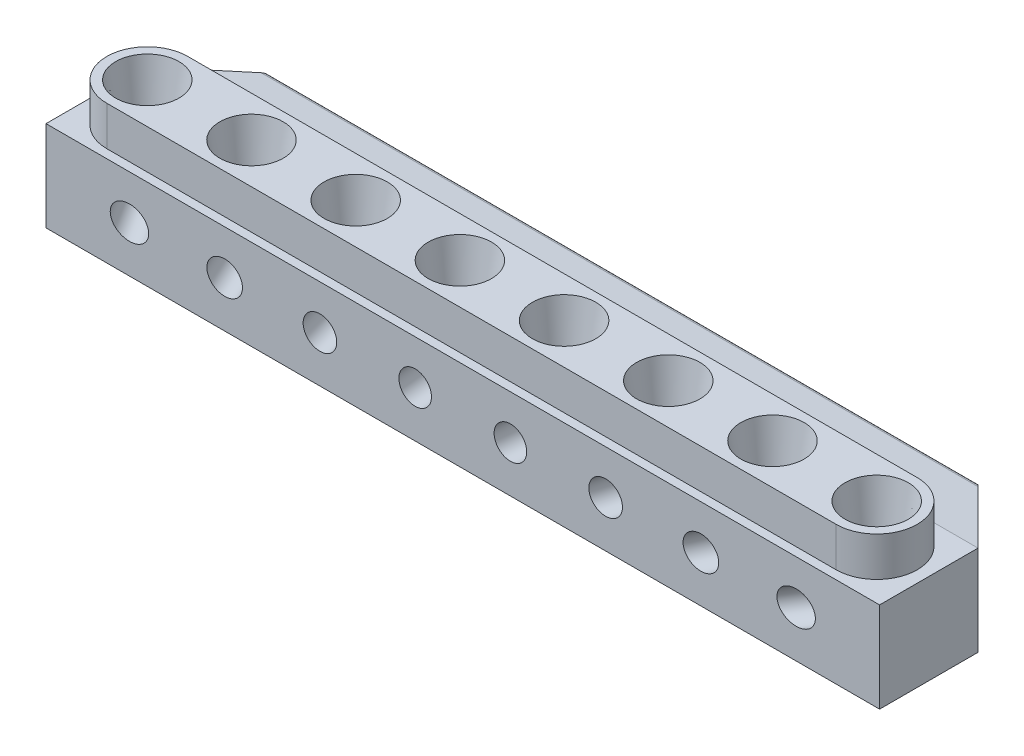
SolidWorks part; units mm, degrees
ref_plane "Front Plane" through (0, 0, 0) normal (0, 0, 1) x (1, 0, 0)
ref_plane "Top Plane" through (0, 0, 0) normal (0, 1, 0) x (1, 0, 0)
ref_plane "Right Plane" through (0, 0, 0) normal (1, 0, 0) x (0, 0, -1)
sketch "Sketch1" plane through (0, 0, 0) normal (0, 1, 0) x (1, 0, 0)
  line L0 (-53.7465, 0) -> (53.7465, 0) construction
  line L1 (-36, 4.25) -> (36, 4.25)
  line L2 (-36, 4.25) -> (-36, -4.25)
  line L3 (-36, -4.25) -> (36, -4.25)
  line L4 (36, 4.25) -> (36, -4.25)
  line L5 (0, 28.9014) -> (0, -25.6338) construction
  dimension "D1" = 8.5
  dimension "D2" = 72
extrude "Boss-Extrude1" add sketch "Sketch1" along normal blind 11.2
ref_plane "Plane1" through (-31.5, 0, 0) normal (-1, 0, 0) x (0, 0, 1)
sketch "Sketch2" plane through (-31.5, 0, 0) normal (-1, 0, 0) x (0, 0, 1)
  line L0 (0, 0) -> (0, 15.76) construction
  line L1 (-2.7346, 11.2) -> (-1.0108, 0)
  line L2 (-4.25, 11.2) -> (4.25, 11.2) construction
  line L4 (-2.7346, 11.2) -> (0, 11.2)
  line L5 (0, 11.2) -> (0, 0)
  line L7 (-4.25, 0) -> (4.25, 0) construction
  line L8 (-1, 0) -> (0, 0)
  line L9 (-3.0651, 13.3473) -> (-1.2355, 1.4598) construction
  line L10 (3.0651, 13.3473) -> (1.2355, 1.4598) construction
  line L11 (-1.1105, 0.4) -> (1.2355, 0.4) construction
  line L12 (-6.929, 4) -> (6.1759, 4) construction
  line L13 (-2.5186, 2.536) -> (2.3279, 2.536) construction
  line L14 (-2.7346, 1.236) -> (2.2226, 1.236) construction
  line L15 (-1, 0) -> (-1.0108, 0)
  arc A1 (-1.2355, 1.4598) -> (1.2355, 1.4598) centre (0, 1.65) ccw construction
  circle A2 centre (0, 2.636) radius 1.4 construction
  circle A3 centre (0, 4.036) radius 1.3 construction
  dimension "D1" = 8.75
  dimension "D3" = 2.5
  dimension "D4" = 0.4
  dimension "D5" = 4
  dimension "D6" = 2.8
  dimension "D8" = 2.6
  dimension "D7" = 1.3
revolve "Cut-Revolve1" cut sketch "Sketch2" angle 360 about L0
pattern_linear "LPattern1" count 8 spacing 9 along (1, 0, 0) of "Cut-Revolve1"
ref_plane "Plane2" through (0, 4, 0) normal (0, -1, 0) x (-1, 0, 0)
sketch "Sketch3" plane through (0, 4, 0) normal (0, -1, 0) x (-1, 0, 0)
  line L0 (31.5, 0) -> (0, -49.4451) construction
  line L1 (0, 0) -> (0, -100.1798) construction
  line L2 (4.5, 0) -> (0, -49.4451) construction
  line L3 (13.5, 0) -> (0, -49.4451) construction
  line L4 (22.5, 0) -> (0, -49.4451) construction
  line L5 (-4.5, 0) -> (0, -49.4451) construction
  line L6 (0, -49.4451) -> (-13.5, 0) construction
  line L7 (-22.5, 0) -> (0, -49.4451) construction
  line L8 (-31.5, 0) -> (0, -49.4451) construction
  dimension "D1" = 32.5
sketch "Sketch7" plane through (-36, 0, 0) normal (-1, 0, 0) x (0, 0, 1)
  line L2 (-4.25, 11.2) -> (4.25, 11.2) construction
  line L22 (-4.25, 7.8) -> (-4.25, 6.1)
  line L23 (-4.25, 3.1) -> (-4.25, 1.4)
  line L29 (-4.25, 3.1) -> (-9.2858, 2.6594)
  line L35 (-4.25, 7.8) -> (-9.2858, 7.3594)
  line L36 (-4.25, 11.2) -> (-4.25, 0) construction
  line L37 (-4.25, 6.95) -> (-14.25, 6.95) construction
  line L38 (-4.25, 6.1) -> (-9.2858, 6.5406)
  line L39 (-4.25, 1.4) -> (-9.2858, 1.8406)
  line L43 (-4.25, -1.6) -> (-4.25, -3.3) [skipped]
  line L44 (-4.25, -3.3) -> (-9.2858, -2.8594) [skipped]
  line L45 (-4.25, -1.6) -> (-9.2858, -2.0406) [skipped]
  arc A0 (-9.2858, 7.3594) -> (-9.2858, 6.5406) centre (-9.25, 6.95) ccw
  arc A1 (-9.2858, 2.6594) -> (-9.2858, 1.8406) centre (-9.25, 2.25) ccw
  arc A3 (-9.2858, -2.0406) -> (-9.2858, -2.8594) centre (-9.25, -2.45) ccw [skipped]
  dimension "D1" = 5
  dimension "D6" = 0.8188
  dimension "D2" = 5
  dimension "D4" = 1.7
  dimension "D3" = 4.25
  dimension "D5" = 3
  dimension "D7" = 3
extrude "Boss-Extrude2" add sketch "Sketch7" against normal up to surface (72 mm away) up to face at (36, 5.6, 0)
sketch "Sketch16" plane through (0, 0, 0) normal (0, -1, 0) x (1, 0, 0)
  line L0 (0, 8.5453) -> (0, -15.5745) construction
  line L1 (0, 0) -> (0, 100.1798) construction
  line L2 (0, 0) -> (-26.7342, 0) construction
  line L3 (-18, 6.6779) -> (-18, -6.0164) construction
  circle A0 centre (-18, 0) radius 1.05
  circle A1 centre (18, 0) radius 1.05
  dimension "D1" = 2.1
  dimension "D2" = 36
extrude "Cut-Extrude9" cut sketch "Sketch16" against normal offset from surface (9.7 mm away) 1.5 up to face at (31.5, 11.2, -2.7346)
sketch "Sketch17" plane through (0, 0, 0) normal (0, 1, 0) x (1, 0, 0)
  line L3 (-36, 4.25) -> (-37.9387, 4.25)
  line L4 (-37.9387, 4.25) -> (-37.9387, 10.603)
  line L5 (-37.9387, 10.603) -> (-29.5049, 10.7451)
  line L6 (-29.5049, 10.7451) -> (-36, 4.25)
  line L7 (0, 0) -> (0, 15.0465) construction
  line L13 (36, 4.25) -> (-36, 4.25) construction
  line L14 (29.5049, 10.7451) -> (36, 4.25)
  line L15 (37.9387, 10.603) -> (29.5049, 10.7451)
  line L16 (37.9387, 4.25) -> (37.9387, 10.603)
  line L17 (36, 4.25) -> (37.9387, 4.25)
  dimension "D1" = 45
extrude "Cut-Extrude11" cut sketch "Sketch17" along normal blind 17
sketch "Sketch21" plane through (0, 0, 0) normal (0, -1, 0) x (1, 0, 0)
  line L0 (-36.8433, 0) -> (37.7538, 0) construction
  line L1 (-34.4, 1.45) -> (34.4, 1.45)
  line L2 (-34.4, 1.45) -> (-34.4, -1.45)
  line L3 (-34.4, -1.45) -> (34.4, -1.45)
  line L4 (34.4, 1.45) -> (34.4, -1.45)
  line L5 (0, 6.4261) -> (0, -12.6306) construction
  line L6 (-31.5, 4.29) -> (-31.5, -4.29) construction
  dimension "D1" = 2.9
  dimension "D2" = 2.9
extrude "Cut-Extrude14" cut sketch "Sketch21" against normal blind 0.7
sketch "Sketch23" plane through (0, 11.2, 0) normal (0, 1, 0) x (1, 0, 0)
  line L4 (36, 4.25) -> (-36, 4.25)
  line L6 (36, 4.25) -> (-36, 4.25)
  line L16 (-31.5, 3.5) -> (31.5, 3.5)
  line L20 (-36, -4.25) -> (36, -4.25)
  line L21 (-36, -4.25) -> (36, -4.25)
  line L24 (31.5, -3.5) -> (-31.5, -3.5)
  line L26 (-36, 4.25) -> (-36, -4.25)
  line L27 (-36, 4.25) -> (-36, -4.25)
  line L30 (36, -4.25) -> (36, 4.25)
  line L31 (36, -4.25) -> (36, 4.25)
  circle A0 centre (31.5, 0) radius 2.7346 construction
  circle A1 centre (22.5, 0) radius 2.7346 construction
  circle A2 centre (13.5, 0) radius 2.7346 construction
  circle A3 centre (4.5, 0) radius 2.7346 construction
  arc A4 (-31.5, 3.5) -> (-31.5, -3.5) centre (-31.5, 0) ccw
  circle A12 centre (-4.5, 0) radius 2.7346 construction
  circle A13 centre (-13.5, 0) radius 2.7346 construction
  circle A14 centre (-22.5, 0) radius 2.7346 construction
  circle A15 centre (-31.5, 0) radius 2.7346 construction
  circle A16 centre (31.5, 0) radius 2.7346 construction
  circle A17 centre (22.5, 0) radius 2.7346 construction
  circle A18 centre (13.5, 0) radius 2.7346 construction
  circle A19 centre (4.5, 0) radius 2.7346 construction
  circle A20 centre (-4.5, 0) radius 2.7346 construction
  circle A21 centre (-13.5, 0) radius 2.7346 construction
  circle A22 centre (-22.5, 0) radius 2.7346 construction
  circle A23 centre (-31.5, 0) radius 2.7346 construction
  arc A40 (31.5, -3.5) -> (31.5, 3.5) centre (31.5, 0) ccw
  dimension "D3" = 7
  dimension "D1" = 0
extrude "Cut-Extrude15" cut sketch "Sketch23" against normal up to vertex (3.4 mm away)
sketch "Sketch24" plane through (0, 0.7, 0) normal (0, -1, 0) x (1, 0, 0)
  line L0 (0, 10.3962) -> (0, -14.1503) construction
  circle A0 centre (-18, 0) radius 1.65
  circle A1 centre (18, 0) radius 1.65
  dimension "D1" = 3.3
extrude "Cut-Extrude16" [suppressed] cut sketch "Sketch24" along normal blind 0.2
ref_plane "Plane12" through (0, 10.7, 0) normal (0, 1, 0) x (1, 0, 0)
sketch "Sketch30" plane through (0, 10.7, 0) normal (0, 1, 0) x (1, 0, 0)
  line L0 (-29.7832, 3.05) -> (-24.2168, 3.05)
  line L1 (36, 4.25) -> (-36, 4.25) construction
  line L2 (-31.5, -3.5) -> (-31.5, -4.421)
  line L3 (-31.5, -4.421) -> (-22.5, -4.421)
  line L4 (-22.5, -4.421) -> (-22.5, -3.5)
  arc A0 (-31.5, -3.5) -> (-29.7832, 3.05) centre (-31.5, 0) ccw
  arc A1 (-24.2168, 3.05) -> (-22.5, -3.5) centre (-22.5, 0) ccw
  dimension "D1" = 7
  dimension "D2" = 1.2
extrude "Cut-Extrude17" [suppressed] cut sketch "Sketch30" against normal blind 5.2
sketch "Sketch31" plane through (0, 11.2, 0) normal (0, 1, 0) x (1, 0, 0)
  line L2 (31.5, 3.5) -> (-31.5, 3.5)
  line L16 (31.5, 3.5) -> (-31.5, 3.5)
  line L18 (-31.5, -3.5) -> (31.5, -3.5)
  line L20 (-31.5, -3.5) -> (31.5, -3.5)
  circle A2 centre (-31.5, 0) radius 3.3346
  circle A3 centre (-31.5, 0) radius 3.3346
  circle A4 centre (22.5, 0) radius 3.3346
  circle A5 centre (22.5, 0) radius 3.3346
  arc A6 (-31.5, 3.5) -> (-31.5, -3.5) centre (-31.5, 0) ccw
  circle A7 centre (31.5, 0) radius 3.3346
  circle A8 centre (31.5, 0) radius 3.3346
  arc A9 (-31.5, 3.5) -> (-31.5, -3.5) centre (-31.5, 0) ccw
  arc A10 (31.5, -3.5) -> (31.5, 3.5) centre (31.5, 0) ccw
  arc A24 (31.5, -3.5) -> (31.5, 3.5) centre (31.5, 0) ccw
  circle A33 centre (-22.5, 0) radius 3.3346
  circle A34 centre (-22.5, 0) radius 3.3346
  circle A36 centre (-13.5, 0) radius 3.3346
  circle A37 centre (-13.5, 0) radius 3.3346
  circle A39 centre (-4.5, 0) radius 3.3346
  circle A40 centre (-4.5, 0) radius 3.3346
  circle A42 centre (4.5, 0) radius 3.3346
  circle A43 centre (4.5, 0) radius 3.3346
  circle A45 centre (13.5, 0) radius 3.3346
  circle A46 centre (13.5, 0) radius 3.3346
  dimension "D1" = 0.6
  dimension "D2" = 0
  dimension "D3" = 0.6
  dimension "D4" = 0.6
  dimension "D5" = 0.6
  dimension "D6" = 0.6
  dimension "D7" = 0.6
  dimension "D8" = 0.6
  dimension "D9" = 0.6
extrude "Cut-Extrude18" [suppressed] cut sketch "Sketch31" against normal up to vertex
sketch "Sketch32" plane through (0, 0.7, 0) normal (0, -1, 0) x (1, 0, 0)
  line L6 (10.2, 1.45) -> (10.2, -1.45) construction
  line L7 (36, 4.25) -> (36, -4.25) construction
  line L8 (4.5, 0) -> (13.5, 0) construction
  circle A0 centre (9, 0) radius 0.8
  dimension "D2" = 1.6
  dimension "D1" = 25.8
ref_plane "Plane13" through (0, 4, 49.4451) normal (-0.5373, 0, -0.8434) x (-0.8434, 0, 0.5373)
ref_plane "Plane14" through (0, 4, 49.4451) normal (0.4142, 0, 0.9102) x (0.9102, 0, -0.4142)
ref_plane "Plane16" through (0, 4, 49.4451) normal (0.2634, 0, 0.9647) x (0.9647, 0, -0.2634)
ref_plane "Plane18" through (0, 4, 49.4451) normal (0.0906, 0, 0.9959) x (0.9959, 0, -0.0906)
sketch "Sketch34" plane through (0, 4, 49.4451) normal (-0.5373, 0, -0.8434) x (-0.8434, 0, 0.5373)
  line L0 (-53.1337, 0) -> (0, 0) construction
  circle A0 centre (0, 0) radius 1.4
extrude "Cut-Extrude20" cut sketch "Sketch34" along normal up to next
sketch "Sketch35" plane through (0, 4, 49.4451) normal (0.4142, 0, 0.9102) x (0.9102, 0, -0.4142)
  line L0 (49.1504, 0) -> (0, 0) construction
  circle A0 centre (0, 0) radius 1.4
sketch "Sketch36" plane through (0, 4, 49.4451) normal (0.2634, 0, 0.9647) x (0.9647, 0, -0.2634)
  circle A0 centre (0, 0) radius 1.4
extrude "Cut-Extrude21" cut sketch "Sketch35" against normal up to next
extrude "Cut-Extrude22" cut sketch "Sketch36" against normal up to next
sketch "Sketch38" plane through (0, 4, 49.4451) normal (0.0906, 0, 0.9959) x (0.9959, 0, -0.0906)
  circle A0 centre (0, 0) radius 1.4
extrude "Cut-Extrude25" cut sketch "Sketch38" against normal up to next
mirror "Mirror2" about plane through (0, 0, 0) normal (1, 0, 0) of "Cut-Extrude25", "Cut-Extrude22", "Cut-Extrude21", "Cut-Extrude20"
extrude "Cut-Extrude26" cut sketch "Sketch32" against normal blind 6
sketch "Sketch39" plane through (0, 0, 0) normal (0, -1, 0) x (1, 0, 0)
  line L0 (34.4, 1.45) -> (-34.4, 1.45) construction
  line L1 (-34.4, -1.45) -> (34.4, -1.45)
  line L4 (-36, 4.25) -> (-36, -4.25)
  line L5 (-36, -4.25) -> (36, -4.25)
  line L6 (36, -4.25) -> (36, 4.25)
  line L7 (36, 4.25) -> (-36, 4.25)
  line L8 (-36, 4.25) -> (-36, -4.25)
  line L9 (-36, -4.25) -> (36, -4.25)
  line L10 (36, -4.25) -> (36, 4.25)
  line L11 (36, 4.25) -> (-36, 4.25)
  line L16 (34.4, 1.45) -> (-34.4, 1.45)
  line L19 (-34.4, 1.45) -> (-34.4, -1.45)
  line L20 (-34.4, -1.45) -> (34.4, -1.45)
  line L23 (34.4, -1.45) -> (34.4, 1.45)
  line L24 (34.4, 1.45) -> (-34.4, 1.45)
  line L27 (-34.4, 1.45) -> (-34.4, -1.45)
  line L31 (34.4, -1.45) -> (34.4, 1.45)
  dimension "D1" = 0
  dimension "D2" = 0
extrude "Boss-Extrude3" [suppressed] add sketch "Sketch39" along normal blind 0.4
equation "\"myAngle\"=1.4"
equation "\"camHole\"= 2.8"
